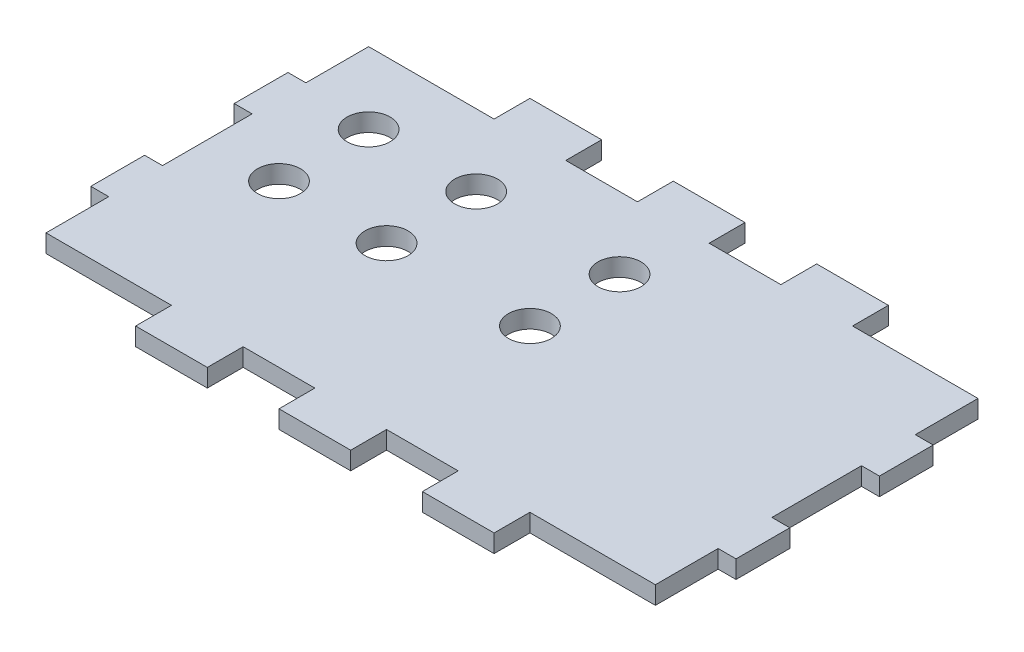
SolidWorks part; units mm, degrees
ref_plane "Plan de face" through (0, 0, 0) normal (0, 0, 1) x (1, 0, 0)
ref_plane "Plan de dessus" through (0, 0, 0) normal (0, 1, 0) x (1, 0, 0)
ref_plane "Plan de droite" through (0, 0, 0) normal (1, 0, 0) x (0, 0, -1)
sketch "Esquisse1" plane through (0, 0, 0) normal (0, 1, 0) x (1, 0, 0)
  line L1 (-90, 55) -> (90, 55)
  line L2 (-90, 55) -> (-90, -55)
  line L3 (-90, -55) -> (90, -55)
  line L4 (90, 55) -> (90, -55)
  line L5 (-90, 55) -> (90, -55) construction
  line L6 (-90, -55) -> (90, 55) construction
  point P0 (0, 0)
  dimension "D1" = 180
  dimension "D2" = 110
extrude "Boss.-Extru.1" add sketch "Esquisse1" along normal blind 5
sketch "Esquisse2" plane through (0, 5, 0) normal (0, 1, 0) x (1, 0, 0)
  line L0 (-90, -55) -> (90, -55) construction
  line L1 (-10, -55) -> (10, -55)
  line L2 (-10, -55) -> (-10, -45)
  line L3 (-10, -45) -> (10, -45)
  line L4 (10, -55) -> (10, -45)
  line L5 (90, 55) -> (-90, 55) construction
  line L6 (30, -55) -> (50, -55)
  line L7 (30, -55) -> (30, -45)
  line L8 (30, -45) -> (50, -45)
  line L9 (50, -55) -> (50, -45)
  line L10 (-50, -55) -> (-30, -55)
  line L11 (-50, -55) -> (-50, -45)
  line L12 (-50, -45) -> (-30, -45)
  line L13 (-30, -55) -> (-30, -45)
  line L14 (-50, 55) -> (-30, 55)
  line L15 (-50, 55) -> (-50, 45)
  line L16 (-50, 45) -> (-30, 45)
  line L17 (-30, 55) -> (-30, 45)
  line L18 (90, -55) -> (90, 55) construction
  line L19 (-10, 55) -> (10, 55)
  line L20 (-10, 55) -> (-10, 45)
  line L21 (-10, 45) -> (10, 45)
  line L22 (10, 55) -> (10, 45)
  line L23 (30, 55) -> (50, 55)
  line L24 (30, 55) -> (30, 45)
  line L25 (30, 45) -> (50, 45)
  line L26 (50, 55) -> (50, 45)
  line L27 (90, 27.5) -> (85, 27.5)
  line L28 (90, 27.5) -> (90, 12.5)
  line L29 (90, 12.5) -> (85, 12.5)
  line L30 (85, 27.5) -> (85, 12.5)
  line L31 (-90, 55) -> (-90, -55) construction
  line L32 (90, -27.5) -> (85, -27.5)
  line L33 (90, -27.5) -> (90, -12.5)
  line L34 (90, -12.5) -> (85, -12.5)
  line L35 (85, -27.5) -> (85, -12.5)
  line L36 (-90, 27.5) -> (-85, 27.5)
  line L37 (-90, 27.5) -> (-90, 12.5)
  line L38 (-90, 12.5) -> (-85, 12.5)
  line L39 (-85, 27.5) -> (-85, 12.5)
  line L40 (-85, 27.5) -> (-85, 45)
  line L41 (-90, -27.5) -> (-85, -27.5)
  line L42 (-90, -27.5) -> (-90, -12.5)
  line L43 (-90, -12.5) -> (-85, -12.5)
  line L44 (-85, -27.5) -> (-85, -12.5)
  line L45 (-85, 45) -> (-50, 45)
  line L46 (-30, 45) -> (-10, 45)
  line L47 (10, 45) -> (30, 45)
  line L48 (50, 45) -> (85, 45)
  line L49 (85, 45) -> (85, 27.5)
  line L50 (85, 12.5) -> (85, -12.5)
  line L51 (85, -27.5) -> (85, -45)
  line L52 (85, -45) -> (50, -45)
  line L53 (30, -45) -> (10, -45)
  line L54 (-10, -45) -> (-30, -45)
  line L55 (-50, -45) -> (-85, -45)
  line L56 (-85, -45) -> (-85, -27.5)
  line L57 (-85, 12.5) -> (-85, -12.5)
  point P48 (0, 45)
  line M38 (90, -55) -> (90, 55)
  line M39 (90, 55) -> (-90, 55)
  line M40 (-90, 55) -> (-90, -55)
  line M41 (-90, -55) -> (90, -55)
  dimension "D1" = 10
  dimension "D2" = 10
  dimension "D3" = 5
  dimension "D4" = 5
  dimension "D5" = 20
  dimension "D6" = 20
  dimension "D7" = 20
  dimension "D8" = 20
  dimension "D9" = 20
  dimension "D10" = 15
  dimension "D11" = 15
  dimension "D12" = 25
  dimension "D13" = 27.5
extrude "Enlèv. mat.-Extru.1" cut sketch "Esquisse2" against normal blind 5 contours L40 L45 L15 L36 M39 M40 | L48 L49 L27 L26 M38 M39 | L22 L47 L24 M39 | L17 L46 L20 M39 | L57 L38 L43 M40 | L55 L56 L41 L11 M40 M41 | L51 L52 L9 L32 M41 M38 | L29 L50 L34 M38 | L7 L53 L4 M41 | L2 L54 L13 M41
sketch "Esquisse3" plane through (0, 5, 0) normal (0, 1, 0) x (1, 0, 0)
  line L0 (-85, 45) -> (-50, 45) construction
  line L1 (-85, 27.5) -> (-85, 45) construction
  circle A0 centre (-35, 25) radius 6
  circle A1 centre (-35, 0) radius 6
  circle A2 centre (5, 25) radius 6
  circle A3 centre (5, 0) radius 6
  circle A4 centre (-65, 25) radius 6
  circle A5 centre (-65, 0) radius 6
  dimension "D1" = 12
  dimension "D2" = 12
  dimension "D3" = 12
  dimension "D4" = 12
  dimension "D5" = 12
  dimension "D6" = 12
  dimension "D7" = 25
  dimension "D8" = 30
  dimension "D9" = 40
  dimension "D10" = 20
  dimension "D11" = 20
extrude "Enlèv. mat.-Extru.2" cut sketch "Esquisse3" against normal blind 5
